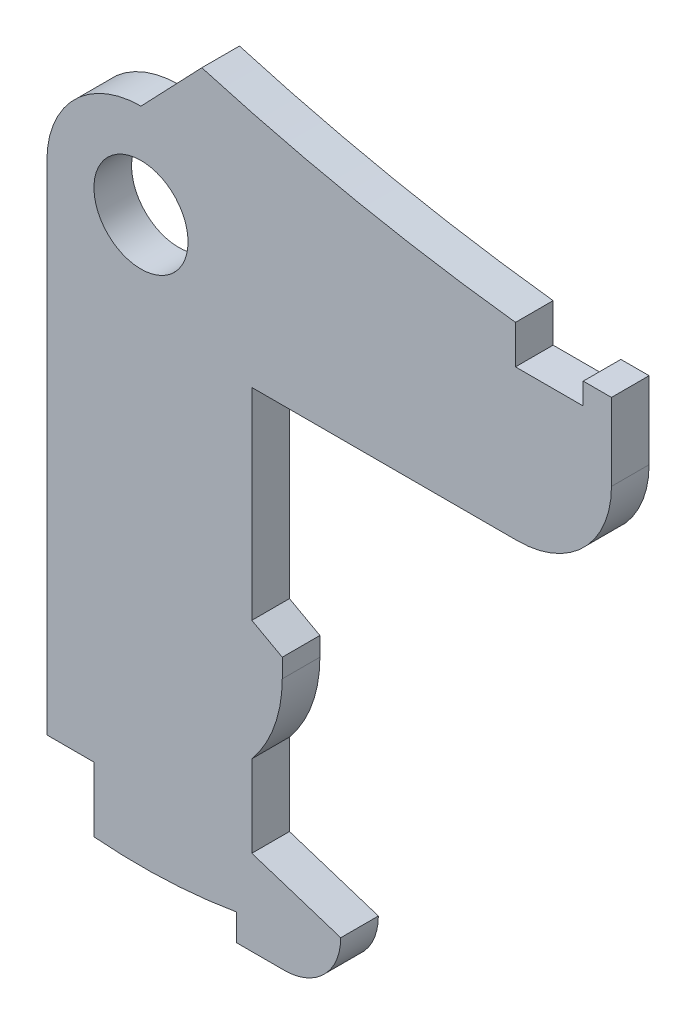
SolidWorks part; units mm, degrees
ref_plane "정면" through (0, 0, 0) normal (0, 0, 1) x (1, 0, 0)
ref_plane "윗면" through (0, 0, 0) normal (0, 1, 0) x (1, 0, 0)
ref_plane "우측면" through (0, 0, 0) normal (1, 0, 0) x (0, 0, -1)
sketch "스케치1" plane through (0, 0, 0) normal (0, 0, 1) x (1, 0, 0)
  line L0 (28.1634, -41.2491) -> (23.65, -39.725)
  line L1 (17.6552, -8.2873) -> (21.1871, -4.904)
  line L2 (53.4867, -33.1492) -> (56.7186, -29.7659)
  line L3 (59.3761, -60.24) -> (59.3761, -64.5868)
  line L4 (73.3867, -33.1492) -> (73.3867, -35.1985)
  line L5 (73.3867, -35.1985) -> (76.9867, -35.1985)
  line L6 (76.9867, -35.1985) -> (76.9867, -34.0533)
  line L7 (76.9867, -34.0533) -> (78.4867, -34.0533)
  line L8 (78.4867, -34.0533) -> (78.4867, -38.1492)
  line L9 (73.4867, -43.1492) -> (59.3761, -43.1492)
  line L10 (59.3761, -43.1492) -> (59.3761, -53.868)
  line L11 (58.5629, -69.1109) -> (61.1004, -69.1109)
  line L12 (48.4867, -64.5869) -> (48.4867, -38.1492)
  line L15 (37.5552, -8.5081) -> (37.5552, -10.3366)
  line L16 (37.5552, -10.3366) -> (41.1552, -10.3366)
  line L18 (50.9867, -68.0237) -> (50.9867, -64.5869)
  line L19 (50.9867, -64.5869) -> (48.4867, -64.5869)
  line L20 (41.1552, -10.3366) -> (41.1552, -9.1914)
  line L21 (41.1552, -9.1914) -> (42.6552, -9.1914)
  line L22 (42.6552, -9.1914) -> (42.6552, -13.2873)
  line L23 (37.6552, -18.2873) -> (23.65, -18.2873)
  line L24 (23.65, -18.2873) -> (23.65, -39.725)
  line L25 (22.7313, -44.2491) -> (25.1634, -44.2491)
  line L26 (12.6552, -39.725) -> (12.6552, -13.2873)
  line L27 (58.5629, -67.6952) -> (58.5629, -69.1109)
  line L28 (59.3761, -60.24) -> (59.3761, -64.5868)
  line L31 (59.3761, -60.24) -> (59.3761, -64.5868)
  line L32 (60.9929, -55.7531) -> (60.9929, -54.7553)
  line L33 (15.1552, -43.1618) -> (15.1552, -39.725)
  line L34 (15.1552, -39.725) -> (12.6552, -39.725)
  line L35 (22.7313, -42.8333) -> (22.7313, -44.2491)
  line L36 (60.9929, -54.7553) -> (59.3761, -53.868)
  line L40 (64.1004, -66.1109) -> (59.3761, -64.5868)
  arc A0 (37.3363, -8.2601) -> (37.5552, -8.5081) centre (37.3052, -8.5081) cw
  arc A1 (25.1634, -44.2491) -> (28.1634, -41.2491) centre (25.1634, -41.2491) ccw
  circle A2 centre (53.4867, -38.1492) radius 2.5
  circle A3 centre (17.6552, -13.2873) radius 2.5
  arc A4 (53.4867, -33.1492) -> (48.4867, -38.1492) centre (53.4867, -38.1492) ccw
  arc A5 (50.9867, -68.0237) -> (58.5629, -67.6952) centre (53.4867, -38.1492) ccw
  arc A6 (17.6552, -8.2873) -> (12.6552, -13.2873) centre (17.6552, -13.2873) ccw
  arc A7 (15.1552, -43.1618) -> (22.7313, -42.8333) centre (17.6552, -13.2873) ccw
  arc A9 (37.3363, -8.2601) -> (21.1871, -4.904) centre (50.2016, 94.181) cw
  arc A10 (42.6552, -13.2873) -> (37.6552, -18.2873) centre (37.6552, -13.2873) cw
  arc A11 (73.3867, -33.1492) -> (56.7186, -29.7659) centre (85.5208, 69.3811) cw
  arc A12 (78.4867, -38.1492) -> (73.4867, -43.1492) centre (73.4867, -38.1492) cw
  arc A13 (60.9929, -55.7531) -> (59.3761, -60.24) centre (53.9584, -55.7531) cw
  arc A14 (61.1004, -69.1109) -> (64.1004, -66.1109) centre (61.1004, -66.1109) ccw
  point P4 (37.5552, -8.2873)
  dimension "D1" = 3.6
  dimension "D2" = 1.5
  dimension "D3" = 103.2458
  dimension "D5" = 5
  dimension "D6" = 5
  dimension "D4" = 0.25
  dimension "D8" = 3
  dimension "D9" = 5
  dimension "D10" = 5
  dimension "D13" = 3
  dimension "D7" = 30
  dimension "D11" = 30
  dimension "D12" = 1.5
  dimension "D17" = 3.6
extrude "보스-돌출1" add sketch "스케치1" along normal blind 2 contours L11 A14 L40 L3 A13 L32 L36 L10 L9 A12 L8 L7 L6 L5 L4 A11 L2 A4 L12 L19 L18 A5 L27 A2
